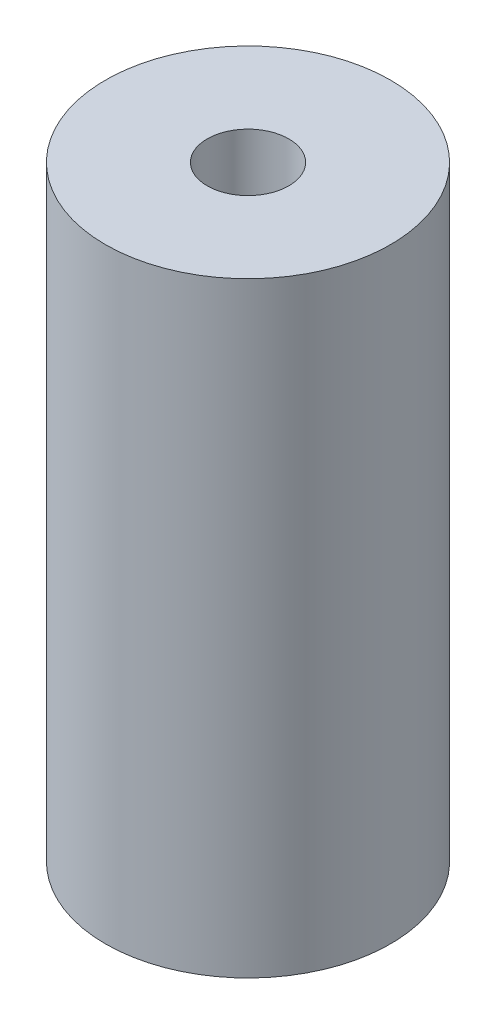
SolidWorks part; units mm, degrees
ref_plane "Front Plane" through (0, 0, 0) normal (0, 0, 1) x (1, 0, 0)
ref_plane "Top Plane" through (0, 0, 0) normal (0, 1, 0) x (1, 0, 0)
ref_plane "Right Plane" through (0, 0, 0) normal (1, 0, 0) x (0, 0, -1)
sketch "Sketch1" plane through (0, 0, 0) normal (0, 1, 0) x (1, 0, 0)
  circle A0 centre (0, 0) radius 7.7724
  circle A1 centre (0, 0) radius 2.2225
  dimension "D1" = 15.5448
  dimension "D2" = 4.445
extrude "Boss-Extrude1" add sketch "Sketch1" along normal blind 33.02
